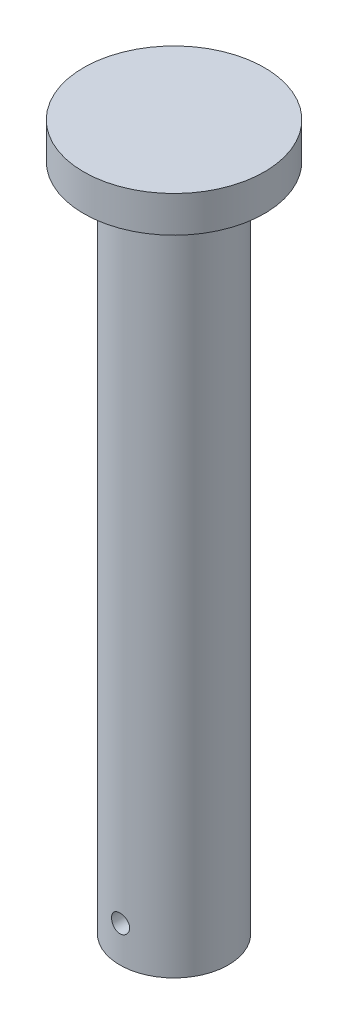
SolidWorks part; units mm, degrees
ref_plane "Front Plane" through (0, 0, 0) normal (0, 0, 1) x (1, 0, 0)
ref_plane "Top Plane" through (0, 0, 0) normal (0, 1, 0) x (1, 0, 0)
ref_plane "Right Plane" through (0, 0, 0) normal (1, 0, 0) x (0, 0, -1)
sketch "Sketch1" plane through (0, 0, 0) normal (0, 1, 0) x (1, 0, 0)
  line L0 (0, 78.349) -> (0, -83.7037) construction
  line L1 (-95.5406, 0) -> (91.3132, 0) construction
  circle A0 centre (0, 0) radius 25
extrude "Boss-Extrude1" add sketch "Sketch1" along normal mid plane 10 contours A0
sketch "Sketch2" plane through (0, -5, 0) normal (0, -1, 0) x (1, 0, 0)
  circle A0 centre (0, 0) radius 15
extrude "Boss-Extrude2" add sketch "Sketch2" along normal blind 185
sketch "Sketch3" plane through (0, 0, 0) normal (0, 0, 1) x (1, 0, 0)
  circle A0 centre (0, -180) radius 2.5
extrude "Cut-Extrude2" cut sketch "Sketch3" against normal mid plane 50
